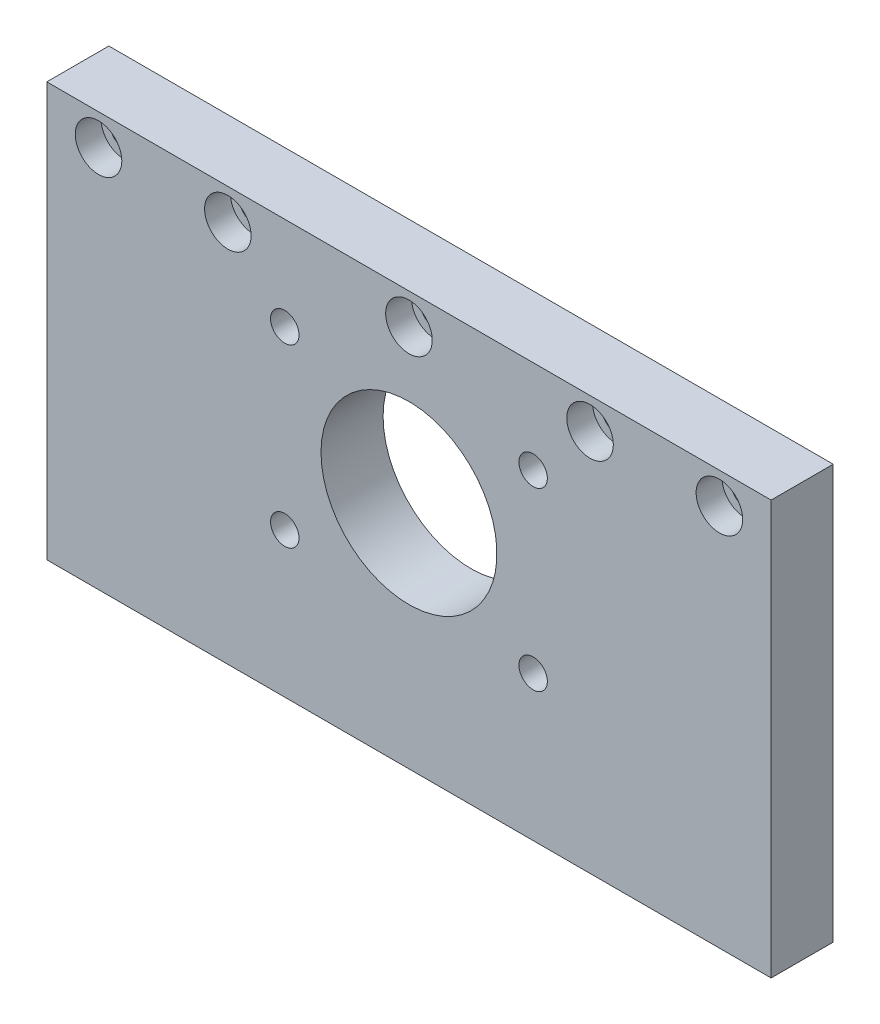
SolidWorks part; units mm, degrees
material "1.0037 (S235JR)"
ref_plane "Płaszczyzna przednia" through (0, 0, 0) normal (0, 0, 1) x (1, 0, 0)
ref_plane "Płaszczyzna górna" through (0, 0, 0) normal (0, 1, 0) x (1, 0, 0)
ref_plane "Płaszczyzna prawa" through (0, 0, 0) normal (1, 0, 0) x (0, 0, -1)
sketch "Szkic1" plane through (0, 0, 0) normal (0, 0, 1) x (1, 0, 0)
  line L0 (-140, 13) -> (-140, 1) construction
  line L1 (0, 13) -> (-140, 13)
  line L2 (0, 13) -> (0, -67)
  line L3 (0, -67) -> (-140, -67)
  line L4 (-140, 13) -> (-140, -67)
  dimension "D1" = 80
extrude "Dodanie-wyciągnięcie1" add sketch "Szkic1" along normal blind 12
hole_wizard "Pogłębienie walcowe pod M5 Wkręt do części metalowych z łbem sześciokątnym1" positions "Szkic3" profile "Szkic2" counterbore size "M5" standard "Ansi Metric" end condition through all
sketch "Szkic3" plane through (0, 0, 12) normal (0, 0, 1) x (1, 0, 0)
  line L0 (0, 7) -> (-140, 7) construction
  line L1 (0, -67) -> (0, 13) construction
  line L2 (-140, 13) -> (-140, -67) construction
  line L4 (0, 13) -> (-140, 13) construction
  point P0 (-10, 7)
  point P2 (-35, 7)
  point P4 (-105, 7)
  point P6 (-130, 7)
  point P20 (-70, 7)
  dimension "D1" = 6
  dimension "D2" = 10
  dimension "D3" = 10
  dimension "D4" = 35
  dimension "D5" = 35
sketch "Szkic2" plane through (-10, 7, 12) normal (1, 0, 0) x (0, -1, 0)
  line L0 (0, 0) -> (0, 12)
  line L1 (0, 12) -> (2.75, 12)
  line L3 (2.75, 12) -> (2.75, 5)
  line L4 (2.75, 5) -> (4.5, 5)
  line L5 (4.5, 5) -> (4.5, 0)
  line L7 (4.5, 0) -> (0, 0)
  line L11 (0, -6.35) -> (0, 107.95) construction
  dimension "Średnica otworu na wylot" = 5.5
  dimension "Głębokość otworu na wylot" = 12
  dimension "Średnica pogłębienia walcowego" = 9
  dimension "Głębokość pogłębienia walcowego" = 5
sketch "Szkic4" plane through (0, 0, 0) normal (0, 0, -1) x (-1, 0, 0)
  circle A1 centre (70, -22.5) radius 17
  circle A2 centre (70, -22.5) radius 16 construction
  dimension "D1" = 34
extrude "Wytnij-wyciągnięcie1" cut sketch "Szkic4" against normal through all
hole_wizard "Pogłębienie walcowe pod M5 Wkręt do części metalowych z łbem sześciokątnym2" positions "Szkic6" profile "Szkic5" counterbore size "M5" standard "Ansi Metric" end condition through all
sketch "Szkic6" plane through (0, 0, 0) normal (0, 0, -1) x (-1, 0, 0)
  circle A0 centre (46, -39) radius 2.1 construction
  circle A1 centre (46, -5) radius 2.1 construction
  point P0 (46, -39)
  point P2 (46, -5)
sketch "Szkic5" plane through (-46, -39, 0) normal (1, 0, 0) x (0, 1, 0)
  line L0 (0, 0) -> (0, 12)
  line L1 (0, 12) -> (2.75, 12)
  line L3 (2.75, 12) -> (2.75, 6)
  line L4 (2.75, 6) -> (4.5, 6)
  line L5 (4.5, 6) -> (4.5, 0)
  line L7 (4.5, 0) -> (0, 0)
  line L11 (0, -6.35) -> (0, 107.95) construction
  dimension "Średnica otworu na wylot" = 5.5
  dimension "Głębokość otworu na wylot" = 12
  dimension "Średnica pogłębienia walcowego" = 9
  dimension "Głębokość pogłębienia walcowego" = 6
ref_plane "Płaszczyzna1" through (-70, 0, 0) normal (-1, 0, 0) x (0, 0, 1)
mirror "Lustro1" about plane through (-70, 0, 0) normal (-1, 0, 0) of "Pogłębienie walcowe pod M5 Wkręt do części metalowych z łbem sześciokątnym2"
equation "\"D3@Szkic3\"=\"D2@Szkic3\""
equation "\"D5@Szkic3\"=\"D4@Szkic3\""
